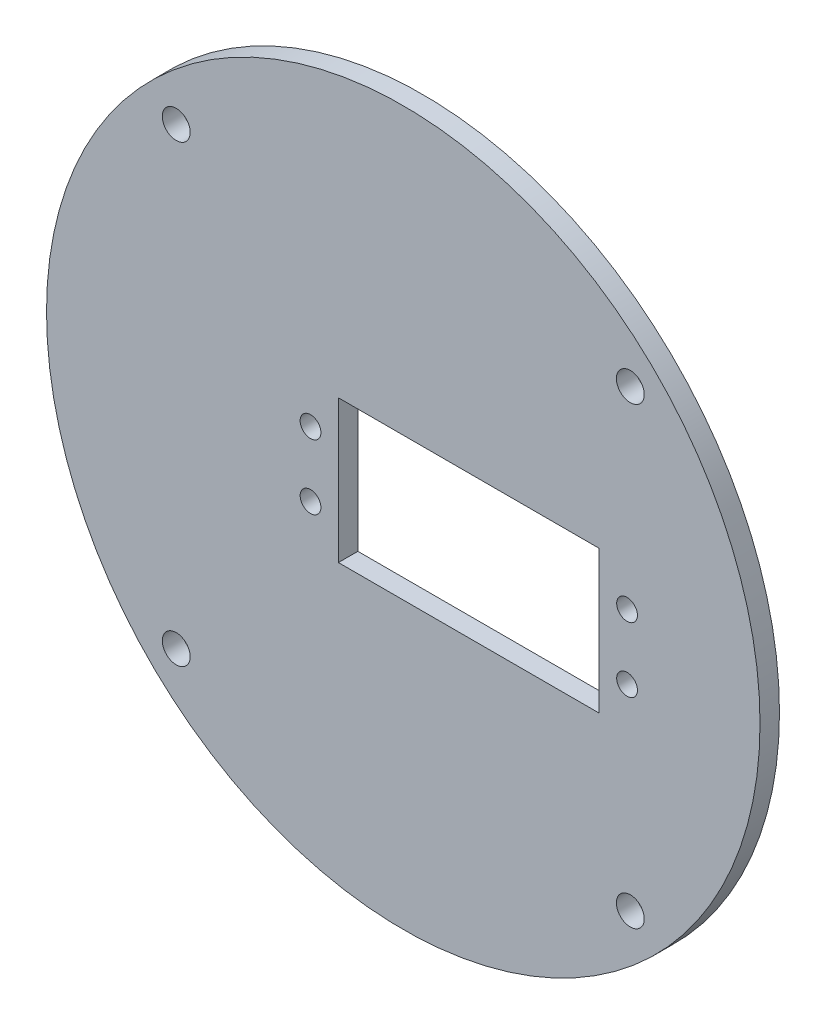
SolidWorks part; units mm, degrees
ref_plane "前视基准面" through (0, 0, 0) normal (0, 0, 1) x (1, 0, 0)
ref_plane "上视基准面" through (0, 0, 0) normal (0, 1, 0) x (1, 0, 0)
ref_plane "右视基准面" through (0, 0, 0) normal (1, 0, 0) x (0, 0, -1)
sketch "草图1" plane through (0, 0, 0) normal (0, 0, 1) x (1, 0, 0)
  line L0 (-35.0018, -35.0018) -> (35.0018, -35.0018)
  line L1 (-35.0018, -35.0018) -> (-35.0018, 35.0018)
  line L2 (-35.0018, 35.0018) -> (35.0018, 35.0018)
  line L3 (35.0018, -35.0018) -> (35.0018, 35.0018)
  line L4 (-35.0018, -35.0018) -> (35.0018, 35.0018) construction
  line L5 (-35.0018, 35.0018) -> (35.0018, -35.0018) construction
  line L7 (-10, 11) -> (30.2, 11)
  line L8 (-10, 11) -> (-10, -11)
  line L9 (-10, -11) -> (30.2, -11)
  line L10 (30.2, 11) -> (30.2, -11)
  line L11 (-14.3, 5) -> (34.5, 5)
  line L12 (-14.3, 5) -> (-14.3, -5)
  line L13 (-14.3, -5) -> (34.5, -5)
  line L14 (34.5, 5) -> (34.5, -5)
  circle A0 centre (0, 0) radius 55
  circle A1 centre (0, 0) radius 45
  circle A2 centre (-35.0018, 35.0018) radius 2.15
  circle A3 centre (35.0018, 35.0018) radius 2.15
  circle A4 centre (35.0018, -35.0018) radius 2.15
  circle A5 centre (-35.0018, -35.0018) radius 2.15
  circle A6 centre (-14.3, 5) radius 1.6
  circle A7 centre (-14.3, -5) radius 1.6
  circle A8 centre (34.5, 5) radius 1.6
  circle A9 centre (34.5, -5) radius 1.6
  point P16 (-10, 0)
  point P21 (-14.3, 0)
  point P22 (10.1, 5)
  point P23 (10.1, 11)
  dimension "D1" = 90
  dimension "D3" = 4.3
  dimension "D4" = 4.3
  dimension "D5" = 4.3
  dimension "D6" = 4.3
  dimension "D7" = 110
  dimension "D14" = 3.2
  dimension "D15" = 3.2
  dimension "D16" = 3.2
  dimension "D17" = 3.2
  dimension "D2" = 99
  dimension "D9" = 40.2
  dimension "D10" = 22
  dimension "D11" = 10
  dimension "D12" = 4.3
  dimension "D13" = 10
extrude "凸台-拉伸2" add sketch "草图1" along normal blind 3 contours A0 A5 L1 A1 A2 L2 A3 L3 A4 L0 | L1 A1 | A9 L13 L10 L9 L8 A7 L12 A6 L11 L7 A8 L3 A1 L2 L1 L0 | L2 A1 | A3 L2 A1 L3 | A9 L3 A1 A8 | L0 A1 | A5 L0 A1 L1 | A7 L13 L8 L11 A6 L12 | A2 L1 A1 L2 | A4 L3 A1 L0 | A9 L14 A8 L11 L10 L13 | A9 L3 A8 L14
